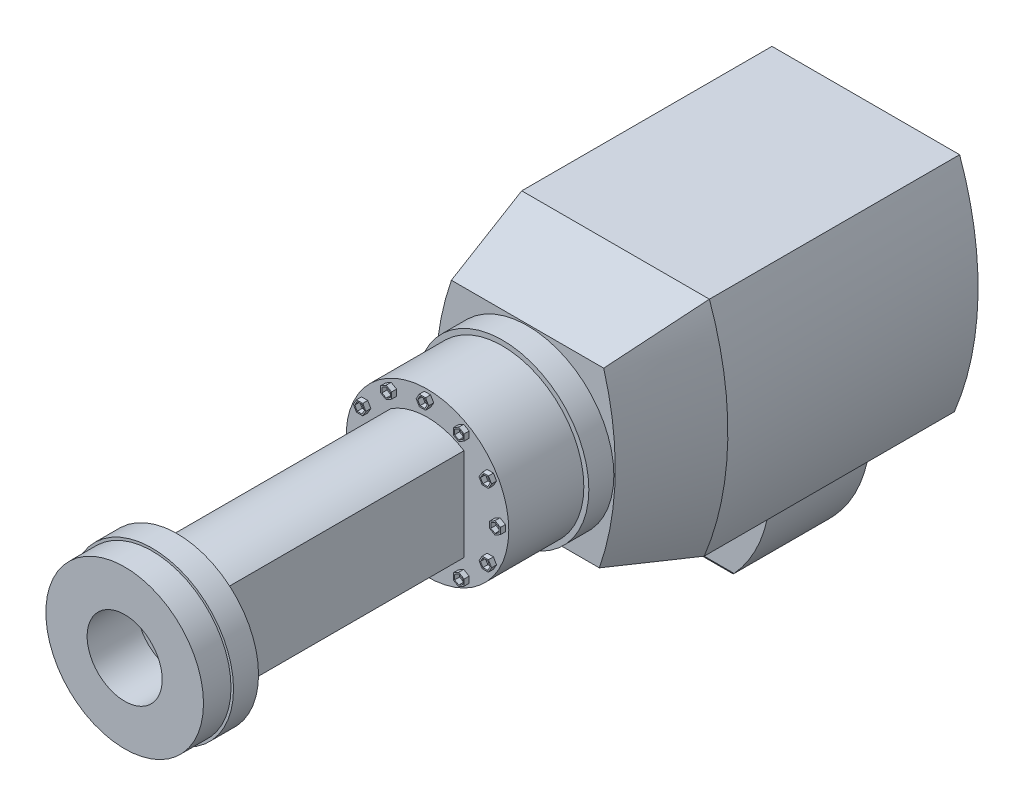
SolidWorks part; units mm, degrees
ref_plane "Front Plane" through (0, 0, 0) normal (0, 0, 1) x (1, 0, 0)
ref_plane "Top Plane" through (0, 0, 0) normal (0, 1, 0) x (1, 0, 0)
ref_plane "Right Plane" through (0, 0, 0) normal (1, 0, 0) x (0, 0, -1)
sketch "Sketch1" plane through (0, 0, 0) normal (0, 0, 1) x (1, 0, 0)
  line L0 (0, -45) -> (0, 45) construction
  line L1 (-28.4007, 45) -> (46.5993, 45)
  line L2 (-30.486, -45) -> (44.514, -45)
  arc A0 (-28.4007, 45) -> (-30.486, -45) centre (87.1397, -2.7012) ccw
  arc A1 (46.5993, 45) -> (44.514, -45) centre (-71.0265, 2.7012) cw
  point P4 (0, 0)
  point P6 (0, 0)
  dimension "D3" = 125
  dimension "D4" = 125
  dimension "D1" = 75
  dimension "D2" = 90
  dimension "D5" = 75
extrude "Boss-Extrude1" add sketch "Sketch1" along normal blind 100
ref_plane "Plane1" through (0, 0, 135) normal (0, 0, 1) x (1, 0, 0)
sketch "Sketch3" plane through (0, 0, 135) normal (0, 0, 1) x (1, 0, 0)
  line L1 (-30.486, -45) -> (44.514, -45) construction
  line L2 (46.5993, 45) -> (-28.4007, 45) construction
  line L3 (-30.486, -45) -> (44.514, -45)
  line L4 (46.5993, 45) -> (-28.4007, 45)
  line L5 (-23.2314, -35) -> (37.618, -35)
  line L6 (39.3447, 35) -> (-21.5047, 35)
  arc A0 (44.514, -45) -> (46.5993, 45) centre (-71.0265, 2.7012) ccw construction
  arc A1 (-28.4007, 45) -> (-30.486, -45) centre (87.1397, -2.7012) ccw construction
  arc A2 (44.514, -45) -> (46.5993, 45) centre (-71.0265, 2.7012) ccw
  arc A3 (-28.4007, 45) -> (-30.486, -45) centre (87.1397, -2.7012) ccw
  arc A4 (-21.5047, 35) -> (-23.2314, -35) centre (87.1397, -2.7012) ccw
  arc A5 (37.618, -35) -> (39.3447, 35) centre (-71.0265, 2.7012) ccw
  dimension "D1" = 10
loft "Loft2" add section "Sketch3" section face at (8.0566, 0, 100)
sketch "Sketch5" plane through (0, 0, 135) normal (0, 0, 1) x (1, 0, 0)
  circle A0 centre (8.92, 0) radius 34.5
  dimension "D1" = 69
extrude "Boss-Extrude2" add sketch "Sketch5" along normal blind 10
sketch "Sketch6" plane through (0, 0, 145) normal (0, 0, 1) x (1, 0, 0)
  circle A2 centre (8.92, 0) radius 32.5
  circle A3 centre (8.92, 0) radius 32.5
  dimension "D1" = 2
extrude "Boss-Extrude3" add sketch "Sketch6" along normal blind 30
sketch "Sketch7" plane through (0, 0, 175) normal (0, 0, 1) x (1, 0, 0)
  line L0 (8.92, 0) -> (37.92, 0) construction
  line L1 (39.5839, 0.9633) -> (37.9177, 1.9226)
  line L2 (37.9171, 2.5) -> (35.7535, 1.2475)
  line L3 (35.7535, 1.2475) -> (35.7564, -1.2525)
  line L4 (35.7564, -1.2525) -> (37.9229, -2.5)
  line L5 (37.9229, -2.5) -> (40.0865, -1.2475)
  line L6 (40.0865, -1.2475) -> (40.0836, 1.2525)
  line L7 (40.0836, 1.2525) -> (37.9171, 2.5)
  line L8 (37.9177, 1.9226) -> (36.2538, 0.9594)
  line L9 (36.2538, 0.9594) -> (36.256, -0.9633)
  line L10 (36.256, -0.9633) -> (37.9222, -1.9226)
  line L11 (37.9222, -1.9226) -> (39.5862, -0.9594)
  line L12 (39.5862, -0.9594) -> (39.5839, 0.9633)
  circle A0 centre (37.92, 0) radius 2.1651 construction
  dimension "D1" = 29
  dimension "D2" = 5
  dimension "D3" = 0.5
extrude "Boss-Extrude4" add sketch "Sketch7" along normal blind 2
pattern_circular "CirPattern1" count 12 over 360 about axis through (8.92, 0, 0) along (0, 0, 1) of "Boss-Extrude4"
sketch "Sketch8" plane through (0, 0, 175) normal (0, 0, 1) x (1, 0, 0)
  line L0 (8.92, 0) -> (23.5043, 0) construction
  line L1 (8.92, 22.5229) -> (8.92, -17.1744) construction
  line L2 (23.5043, 18.5) -> (23.5043, -18.5)
  line L3 (-5.6644, 18.5) -> (-5.6644, -18.5)
  arc A0 (-5.6644, 18.5) -> (23.5043, 18.5) centre (8.92, -4.2222) cw
  arc A1 (-5.6644, -18.5) -> (23.5043, -18.5) centre (8.92, 4.2222) ccw
  point P14 (0, 0)
  dimension "D2" = 27
  dimension "D1" = 37
extrude "Boss-Extrude5" add sketch "Sketch8" along normal blind 100
sketch "Sketch9" plane through (0, 0, 275) normal (0, 0, 1) x (1, 0, 0)
  circle A0 centre (8.92, 0) radius 32.5 construction
  circle A1 centre (8.92, 0) radius 32.5
extrude "Boss-Extrude6" add sketch "Sketch9" along normal blind 10
sketch "Sketch10" plane through (0, 0, 285) normal (0, 0, 1) x (1, 0, 0)
  circle A2 centre (8.92, 0) radius 31.5
  circle A3 centre (8.92, 0) radius 31.5
  dimension "D1" = 1
extrude "Boss-Extrude7" add sketch "Sketch10" along normal blind 1
sketch "Sketch11" plane through (0, 0, 286) normal (0, 0, 1) x (1, 0, 0)
  circle A1 centre (8.92, 0) radius 31.5
  circle A2 centre (8.92, 0) radius 31.5
  dimension "D1" = 0
extrude "Boss-Extrude8" add sketch "Sketch11" along normal blind 10
ref_plane "Plane2" through (-35, 0, 0) normal (1, 0, 0) x (0, 0, -1)
sketch "Sketch12" plane through (-35, 0, 0) normal (1, 0, 0) x (0, 0, -1)
  line L0 (-100, -45) -> (0, -45) construction
  circle A0 centre (-50, -45) radius 42.5
  dimension "D1" = 85
extrude "Boss-Extrude9" add sketch "Sketch12" against normal mid plane 21
sketch "Sketch13" plane through (-24.5, 0, 0) normal (1, 0, 0) x (0, 0, -1)
  line L0 (-50, -45) -> (-50, -75) construction
  line L1 (-100, -45) -> (0, -45) construction
  line L2 (-70, -45) -> (-70, -75)
  line L3 (-30, -45) -> (-30, -75)
  line L4 (-70, -45) -> (-30, -45)
  arc A0 (-70, -75) -> (-30, -75) centre (-50, -60) ccw
  dimension "D4" = 25
  dimension "D1" = 30
  dimension "D2" = 20
  dimension "D3" = 20
extrude "Boss-Extrude10" add sketch "Sketch13" along normal blind 35
ref_plane "Plane3" through (0, 0, 50) normal (0, 0, -1) x (-1, 0, 0)
sketch "Sketch14" plane through (0, 0, 50) normal (0, 0, -1) x (-1, 0, 0)
  line L3 (-10.5, -45) -> (-10.5, -87)
  line L4 (-10.5, -45) -> (-40.5, -45)
  line L5 (30.486, -45) -> (-44.514, -45) construction
  arc A1 (-40.5, -45) -> (-10.5, -87) centre (14.0227, -37.7695) ccw
  dimension "D3" = 42
  dimension "D1" = 55
  dimension "D2" = 30
extrude "Boss-Extrude12" add sketch "Sketch14" along normal mid plane 40
sketch "Sketch15" plane through (10.5, 0, 0) normal (-1, 0, 0) x (0, 0, 1)
  line L3 (70, -87) -> (70, -75)
  line L4 (30, -75) -> (30, -87)
  line L5 (30, -87) -> (70, -87)
  line L6 (70, -87) -> (70, -75)
  line L7 (30, -75) -> (30, -87)
  line L8 (30, -87) -> (70, -87)
  arc A1 (30, -75) -> (70, -75) centre (50, -60) ccw
  arc A2 (30, -75) -> (70, -75) centre (50, -60) ccw
  dimension "D1" = 0
extrude "Cut-Extrude1" cut sketch "Sketch15" against normal blind 40
sketch "Sketch16" plane through (0, 0, 296) normal (0, 0, 1) x (1, 0, 0)
  circle A0 centre (8.92, 0) radius 15
  dimension "D1" = 30
extrude "Cut-Extrude2" cut sketch "Sketch16" against normal blind 20
sketch "Sketch17" plane through (-45.5, 0, 0) normal (-1, 0, 0) x (0, 0, 1)
  circle A0 centre (50, -45) radius 15
  dimension "D1" = 30
extrude "Cut-Extrude3" cut sketch "Sketch17" against normal blind 20
